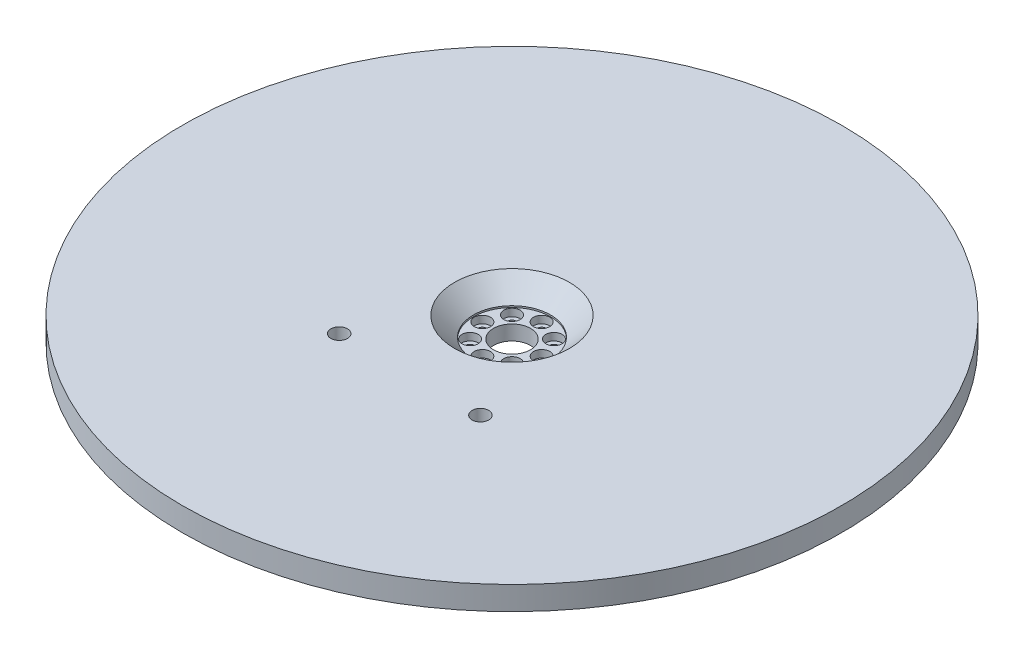
SolidWorks part; units mm, degrees
other "Markup1"
sketch "Sketch21" plane through (-65.5, -15.05, -60) normal (-0.0927, -0.2854, -0.9539) x (0.9951, -0.0609, -0.0785)
material "6061 Alloy"
ref_plane "Front Plane" through (0, 0, 0) normal (0, 0, 1) x (1, 0, 0)
ref_plane "Top Plane" through (0, 0, 0) normal (0, 1, 0) x (1, 0, 0)
ref_plane "Right Plane" through (0, 0, 0) normal (1, 0, 0) x (0, 0, -1)
sketch "Sketch1" plane through (0, 0, 0) normal (0, 1, 0) x (1, 0, 0)
  circle A0 centre (0, 0) radius 88.9
  dimension "D1" = 177.8
extrude "Boss-Extrude1" add sketch "Sketch1" along normal mid plane 6.35
sketch "Sketch2" plane through (0, -3.175, 0) normal (0, -1, 0) x (1, 0, 0)
  circle A0 centre (0, 0) radius 12.065
  circle A1 centre (0, 0) radius 88.9 construction
  dimension "D1" = 24.13
extrude "Boss-Extrude2" add sketch "Sketch2" along normal blind 3.175
sketch "Sketch5" plane through (0, 3.175, 0) normal (0, 1, 0) x (1, 0, 0)
  circle A0 centre (0, 0) radius 10.4
  circle A1 centre (0, 0) radius 88.9 construction
  dimension "D1" = 20.8
extrude "Cut-Extrude1" cut sketch "Sketch5" against normal offset from surface (5.525 mm away) 4 up to face at (0, -6.35, -12.065)
sketch "Sketch6" plane through (0, -2.35, 0) normal (0, 1, 0) x (1, 0, 0)
  circle A0 centre (0, 0) radius 5
  circle A1 centre (0, 0) radius 10.4 construction
  dimension "D1" = 10
extrude "Cut-Extrude2" cut sketch "Sketch6" along direction (0, -1, 0) on the side against the normal up to next (4 mm away)
sketch "Sketch15" plane through (0, -6.35, 0) normal (0, 1, 0) x (1, 0, 0)
  circle A0 centre (0, 8) radius 1
  circle A1 centre (-5.6569, 5.6569) radius 1
  circle A2 centre (5.6569, 5.6569) radius 1
  circle A3 centre (-5.6569, -5.6569) radius 1
  circle A4 centre (5.6569, -5.6569) radius 1
  circle A5 centre (-8, 0) radius 1
  circle A6 centre (0, -8) radius 1
  circle A7 centre (8, 0) radius 1
  circle A8 centre (0, 0) radius 4
  circle A9 centre (0, 0) radius 11
  circle A10 centre (0, 0) radius 2.25
  circle A11 centre (0, 0) radius 5
  circle A12 centre (0, 0) radius 5 construction
  dimension "D1" = 4.5
  dimension "D2" = 8
  dimension "D3" = 10
  dimension "D4" = 22
  dimension "D5" = 2
  dimension "D6" = 8
  dimension "D7" = 5.6569
  dimension "D8" = 8
  dimension "D9" = 5.6569
  dimension "D10" = 5.6569
  dimension "D11" = 8
  dimension "D12" = 5.6569
  dimension "D13" = 8
hole_wizard "CBORE for M2 SHCS1" positions "Sketch19" profile "Sketch20" counterbore size "M2" standard "ANSI Metric"
sketch "Sketch19" plane through (0, -2.35, 0) normal (0, 1, 0) x (1, 0, 0)
  point P0 (-5.6569, 5.6569)
  point P3 (0, 8)
  point P6 (5.6569, 5.6569)
  point P9 (8, 0)
  point P12 (5.6569, -5.6569)
  point P15 (0, -8)
  point P18 (-5.6569, -5.6569)
  point P21 (-8, 0)
sketch "Sketch20" plane through (-5.6569, -2.35, -5.6569) normal (1, 0, 0) x (0, 0, 1)
  line L0 (0, 0) -> (0, 6.6609)
  line L1 (0, 6.6609) -> (1.1, 6)
  line L2 (1.1, 6) -> (1.1, 2)
  line L3 (1.1, 2) -> (2.2, 2)
  line L4 (2.2, 2) -> (2.2, 0)
  line L5 (2.2, 0) -> (0, 0)
  line L10 (0, 6.6609) -> (-1.1, 6) construction
  line L11 (0, -6.35) -> (0, 107.95) construction
  dimension "Hole Dia." = 2.2
  dimension "Hole Depth" = 6
  dimension "C'Bore Dia." = 4.4
  dimension "C'Bore Depth" = 2
  dimension "Drill Angle" = 118
hole_wizard "M4 Clearance Hole1" positions "Sketch26" profile "Sketch27" hole size "M4" standard "ANSI Metric" end condition through all
sketch "Sketch26" plane through (0, 3.175, 0) normal (0, 1, 0) x (1, 0, 0)
  point P0 (19.05, -27.5642)
  point P3 (-19.05, -27.5642)
sketch "Sketch27" plane through (19.05, 3.175, 27.5642) normal (1, 0, 0) x (0, 0, 1)
  line L0 (0, 0) -> (0, 9.525)
  line L1 (0, 9.525) -> (2.25, 9.525)
  line L2 (2.25, 9.525) -> (2.25, 0)
  line L5 (2.25, 0) -> (0, 0)
  line L11 (0, -6.35) -> (0, 107.95) construction
  dimension "Thru Hole Dia." = 4.5
  dimension "Thru Hole Depth" = 9.525
chamfer "Chamfer1" distance 5.08 angle 45 1 edges at (0, 3.175, 10.4)
